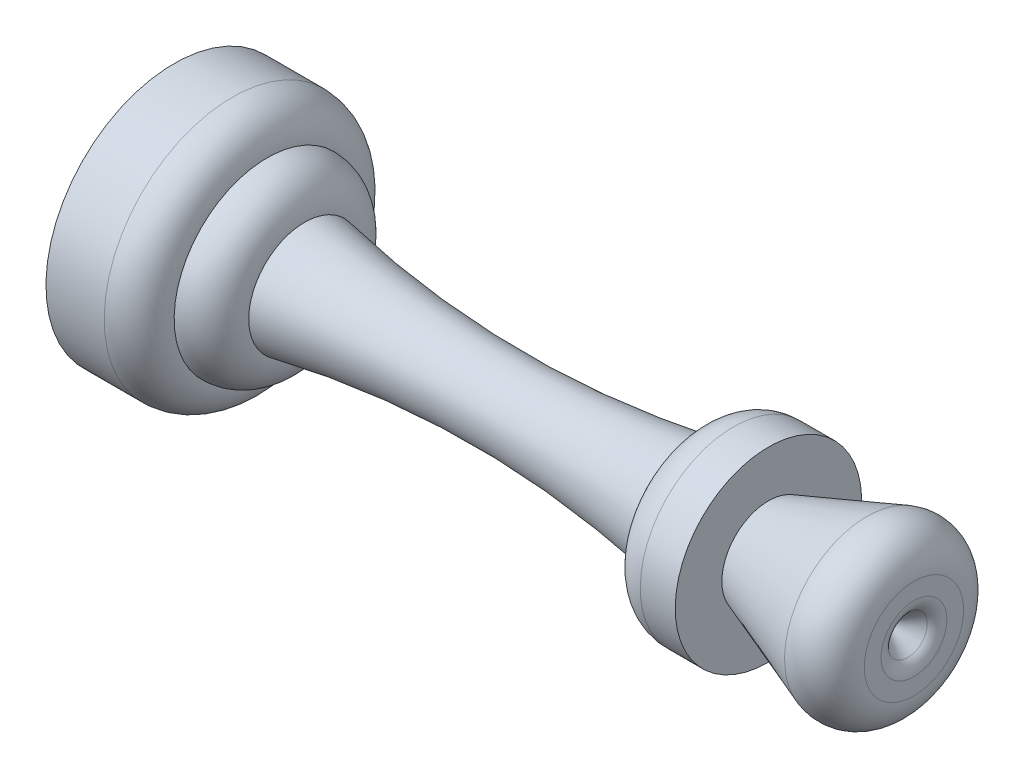
SolidWorks part; units mm, degrees
ref_plane "Спереди" through (0, 0, 0) normal (0, 0, 1) x (1, 0, 0)
ref_plane "Сверху" through (0, 0, 0) normal (0, 1, 0) x (1, 0, 0)
ref_plane "Справа" through (0, 0, 0) normal (1, 0, 0) x (0, 0, -1)
other "Configuration Table"
sketch "Эскиз1" plane through (0, 0, 0) normal (0, 0, 1) x (1, 0, 0)
  line L0 (0, 11) -> (60.9499, 11) construction
  line L1 (0, 0) -> (5, 0)
  line L2 (0, 0) -> (0, 11)
  line L4 (5, 0) -> (5, 11)
  line L6 (5, 11) -> (5, 3)
  line L7 (5, 3) -> (8, 3)
  line L8 (8, 11) -> (8, 3)
  line L10 (8, 11) -> (8, 6.2)
  line L12 (48, 11) -> (48, 6.2)
  line L13 (48, 3) -> (51, 3)
  line L14 (48, 3) -> (48, 11)
  line L16 (51, 3) -> (51, 11)
  line L18 (51, 9.7865) -> (51, 9)
  line L20 (51, 7) -> (59.4572, 3.9218)
  line L21 (63.4833, 6.7409) -> (63.4833, 8.1747)
  line L22 (62.9475, 9.3238) -> (60.9499, 11)
  line L25 (0, 11) -> (60.9499, 11)
  arc A0 (5, 0) -> (8, 3) centre (5, 3) ccw
  arc A1 (8, 3) -> (11.2, 6.2) centre (8, 6.2) ccw
  arc A2 (48, 3) -> (44.8, 6.2) centre (48, 6.2) cw
  arc A3 (63.4833, 6.7409) -> (59.4572, 3.9218) centre (60.4833, 6.7409) cw
  arc A4 (63.4833, 8.1747) -> (62.9475, 9.3238) centre (61.9833, 8.1747) ccw
  arc A5 (11.2, 6.2) -> (44.8, 6.2) centre (28, -81.2) cw
  dimension "D8" = 3
  dimension "D9" = 3.2
  dimension "D15" = 3.2
  dimension "D19" = 9
  dimension "D16" = 3
  dimension "D12" = 3
  dimension "D14" = 6.7865
  dimension "D17" = 4.8
  dimension "D22" = 4.8
  dimension "D25" = 89
  dimension "D2" = 5
  dimension "D3" = 3
  dimension "D4" = 60.9499
  dimension "D5" = 3
  dimension "D7" = 3.2
  dimension "D10" = 40
  dimension "D11" = 3.2
  dimension "D18" = 6
  dimension "D20" = 4
  dimension "D21" = 70
  dimension "D26" = 3.2
  dimension "D27" = 3.2
revolve "Повернуть1" add sketch "Эскиз1" angle 360 about L0
